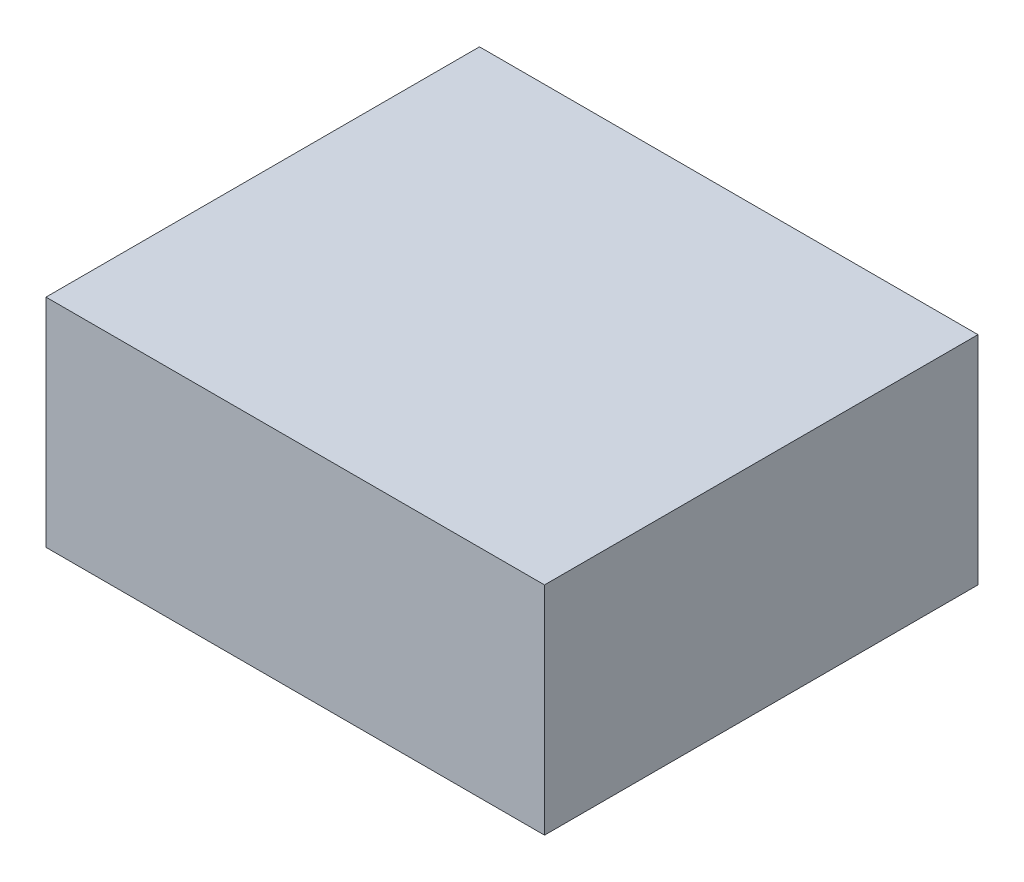
SolidWorks part; units mm, degrees
ref_plane "Front Plane" through (0, 0, 0) normal (0, 0, 1) x (1, 0, 0)
ref_plane "Top Plane" through (0, 0, 0) normal (0, 1, 0) x (1, 0, 0)
ref_plane "Right Plane" through (0, 0, 0) normal (1, 0, 0) x (0, 0, -1)
sketch "Sketch1" plane through (0, 0, 0) normal (0, 1, 0) x (1, 0, 0)
  line L1 (0, 0) -> (23, 0)
  line L2 (0, 0) -> (0, 20)
  line L3 (0, 20) -> (23, 20)
  line L4 (23, 0) -> (23, 20)
extrude "Boss-Extrude1" add sketch "Sketch1" along normal blind 10
